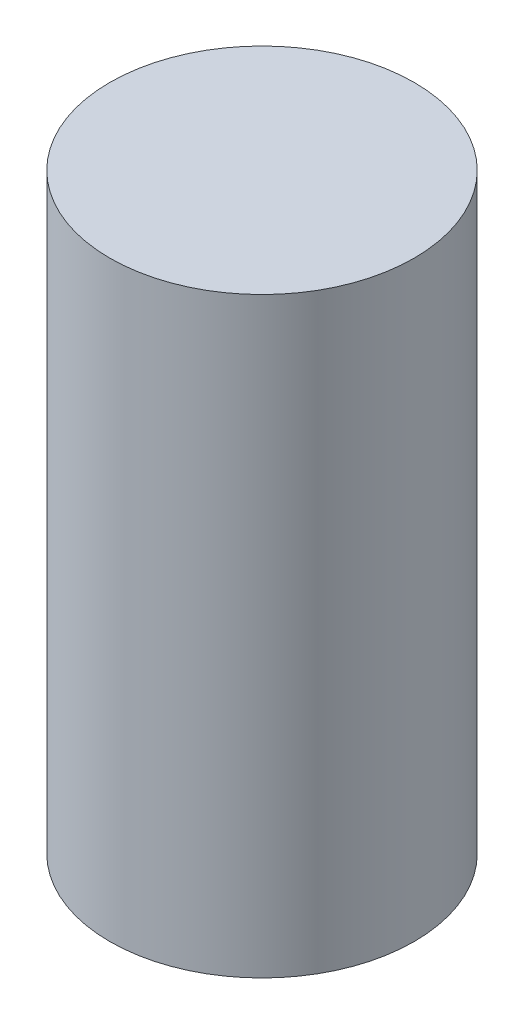
SolidWorks part; units mm, degrees
ref_plane "Front Plane" through (0, 0, 0) normal (0, 0, 1) x (1, 0, 0)
ref_plane "Top Plane" through (0, 0, 0) normal (0, 1, 0) x (1, 0, 0)
ref_plane "Right Plane" through (0, 0, 0) normal (1, 0, 0) x (0, 0, -1)
sketch "Sketch1" plane through (0, 0, 0) normal (0, 1, 0) x (1, 0, 0)
  circle A0 centre (0, 0) radius 36
  dimension "D1" = 72
extrude "Boss-Extrude1" add sketch "Sketch1" along normal blind 140
